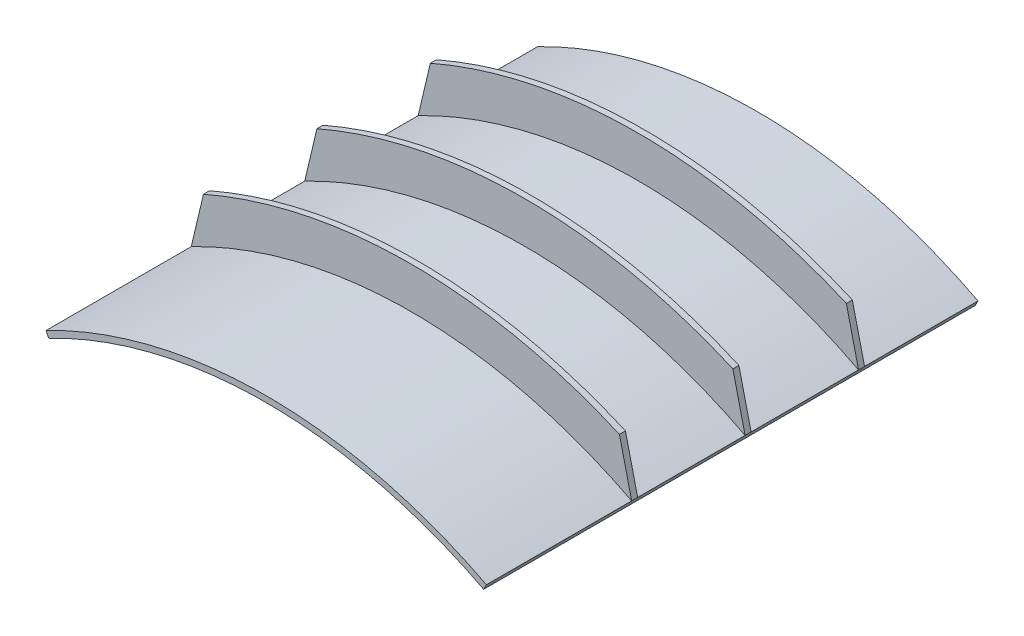
SolidWorks part; units mm, degrees
ref_plane "Front Plane" through (0, 0, 0) normal (0, 0, 1) x (1, 0, 0)
ref_plane "Top Plane" through (0, 0, 0) normal (0, 1, 0) x (1, 0, 0)
ref_plane "Right Plane" through (0, 0, 0) normal (1, 0, 0) x (0, 0, -1)
sketch "Sketch1" plane through (0, 0, 0) normal (0, 0, 1) x (1, 0, 0)
  line L0 (-116.4605, 224.7989) -> (-115, 221.9797)
  line L1 (115, 221.9797) -> (116.4605, 224.7989)
  arc A0 (-116.4605, 224.7989) -> (116.4605, 224.7989) centre (0, 0) cw
  arc A1 (-115, 221.9797) -> (115, 221.9797) centre (0, 0) cw
  dimension "D1" = 250
  dimension "D2" = 253.175
  dimension "D3" = 230
  dimension "D4" = 115
extrude "Boss-Extrude1" add sketch "Sketch1" along normal blind 260
sketch "Sketch2" plane through (0, 0, 0) normal (0, 0, 1) x (1, 0, 0)
  line L0 (115, 221.9797) -> (116.4605, 224.7989) construction
  line L1 (-110, 252.0417) -> (-116.4605, 224.7989)
  line L3 (116.4605, 224.7989) -> (110, 252.0417)
  arc A0 (-116.4605, 224.7989) -> (116.4605, 224.7989) centre (0, 0) cw
  arc A1 (-110, 252.0417) -> (110, 252.0417) centre (0, 0) cw
  dimension "D1" = 275
  dimension "D2" = 110
  dimension "D3" = 110
extrude "Boss-Extrude2" add sketch "Sketch2" along normal blind 3.175 from offset 60
pattern_linear "LPattern1" count 3 spacing 60 along (0, 0, 1) of "Boss-Extrude2"
